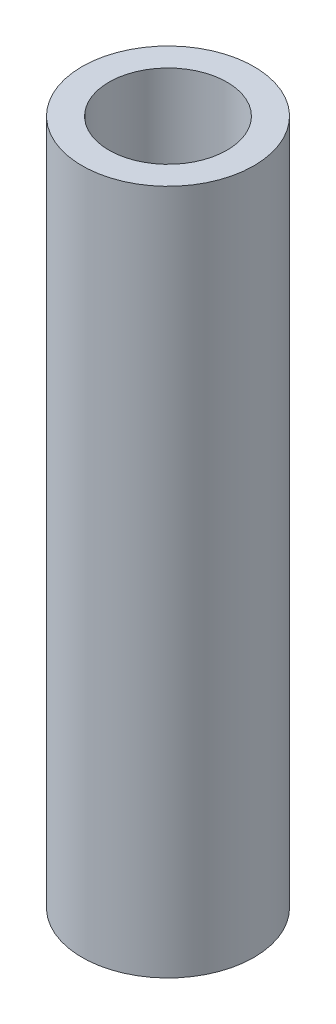
SolidWorks part; units mm, degrees
material "Rubber"
ref_plane "Front Plane" through (0, 0, 0) normal (0, 0, 1) x (1, 0, 0)
ref_plane "Top Plane" through (0, 0, 0) normal (0, 1, 0) x (1, 0, 0)
ref_plane "Right Plane" through (0, 0, 0) normal (1, 0, 0) x (0, 0, -1)
sketch "Sketch1" plane through (0, 0, 0) normal (0, 1, 0) x (1, 0, 0)
  circle A0 centre (0, 0) radius 6.025
extrude "Extrude-Thin1" add sketch "Sketch1" along normal blind 70 thin
